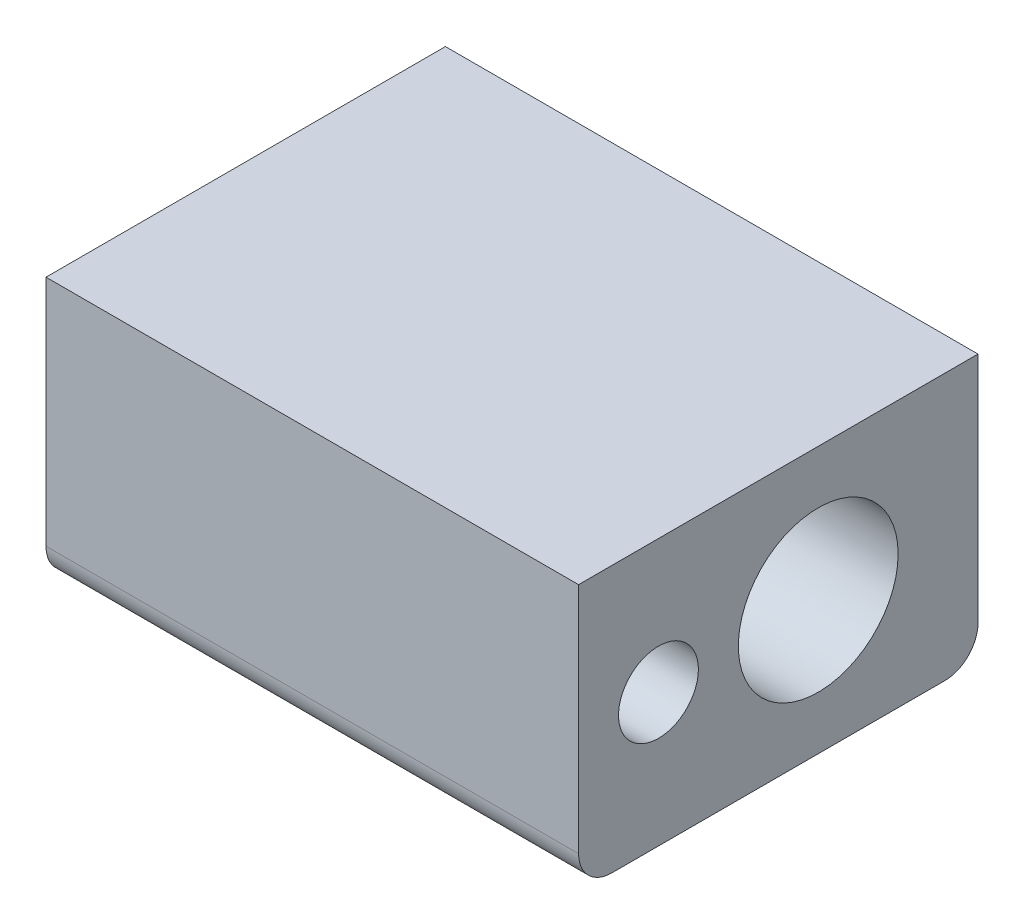
SolidWorks part; units mm, degrees
ref_plane "Front Plane" through (0, 0, 0) normal (1, 0, 0) x (0, 1, 0)
ref_plane "Top Plane" through (0, 0, 0) normal (0, 0, 1) x (0, 1, 0)
ref_plane "Right Plane" through (0, 0, 0) normal (0, 1, 0) x (-1, 0, 0)
sketch "Sketch1" plane through (0, 0, 0) normal (1, 0, 0) x (0, 1, 0)
  line L0 (0, -41.91) -> (0, 41.91) construction
  line L1 (25.4, -38.1) -> (-25.4, -38.1)
  line L2 (25.4, -38.1) -> (25.4, 38.1)
  line L3 (25.4, 38.1) -> (-25.4, 38.1)
  line L4 (-25.4, -38.1) -> (-25.4, 38.1)
  line L5 (25.4, -38.1) -> (-25.4, 38.1) construction
  line L6 (25.4, 38.1) -> (-25.4, -38.1) construction
  circle A0 centre (0, -7.62) radius 15.24
  circle A1 centre (0, 22.86) radius 7.62
  point P0 (0, 0)
  dimension "D3" = 30.48
  dimension "D5" = 15.24
  dimension "D1" = 50.8
  dimension "D2" = 76.2
  dimension "D4" = 30.48
  dimension "D6" = 15.24
extrude "Boss-Extrude1" add sketch "Sketch1" along normal blind 101.6
fillet "Fillet1" radius 6.35 2 edges at (50.8, -25.4, -38.1) (50.8, -25.4, 38.1)
